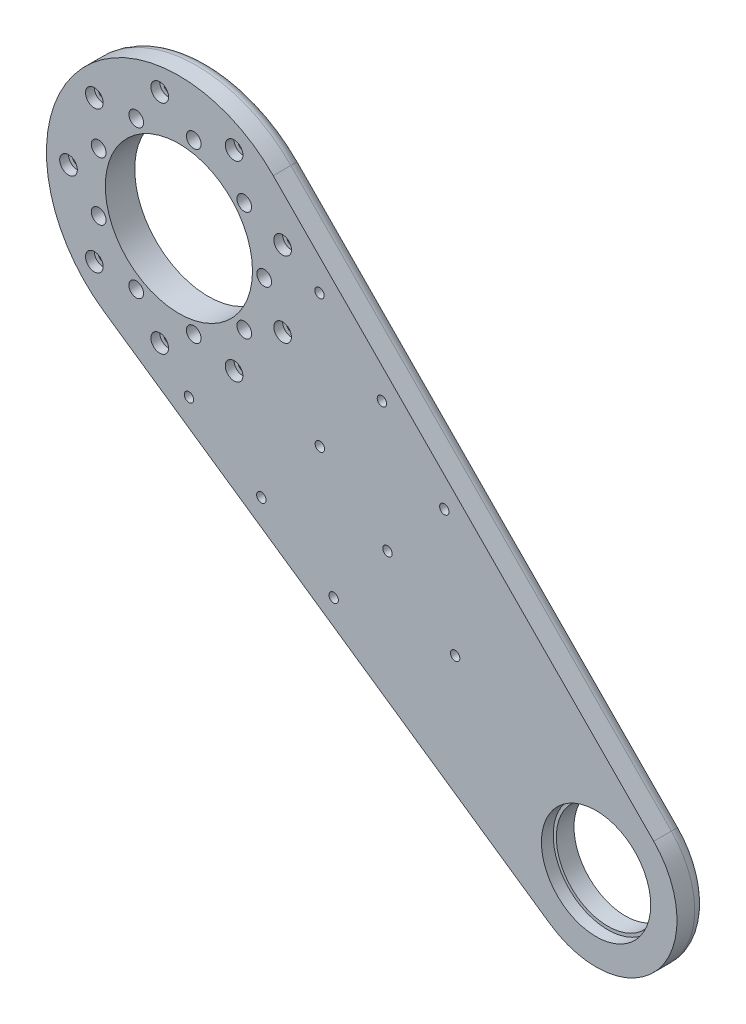
SolidWorks part; units mm, degrees
material "ABS"
ref_plane "Front Plane" through (0, 0, 0) normal (0, 0, 1) x (1, 0, 0)
ref_plane "Top Plane" through (0, 0, 0) normal (0, 1, 0) x (1, 0, 0)
ref_plane "Right Plane" through (0, 0, 0) normal (1, 0, 0) x (0, 0, -1)
sketch "Sketch1" plane through (0, 0, 0) normal (0, 0, 1) x (1, 0, 0)
  line L0 (141.7182, -118.9157) -> (13.1607, -272.1246) construction
  line L1 (26.7138, 26.3177) -> (155.9656, -104.8796) construction
  line L2 (-25.5349, -37.0536) -> (126.1136, -141.5596)
  line L3 (32.0566, 31.5812) -> (161.3084, -99.6161)
  line L4 (-21.2791, -30.878) -> (130.3694, -135.384) construction
  line L5 (0, 0) -> (141.7182, -118.9157) construction
  arc A0 (32.0566, 31.5812) -> (-25.5349, -37.0536) centre (0, 0) ccw
  arc A1 (126.1136, -141.5596) -> (161.3084, -99.6161) centre (141.7182, -118.9157) ccw
  circle A5 centre (0, 0) radius 25 construction
  circle A6 centre (0, 0) radius 37.5 construction
  circle A7 centre (141.7182, -118.9157) radius 17.5
  circle A8 centre (70.8591, -59.4579) radius 1.6
  circle A9 centre (93.8404, -78.7415) radius 1.6
  circle A10 centre (47.8778, -40.1742) radius 1.6
  circle A11 centre (141.7182, -118.9157) radius 20 construction
  circle A12 centre (47.768, 4.9466) radius 1.6
  circle A14 centre (3.4233, -47.9013) radius 1.6
  circle A16 centre (68.9739, -16.2739) radius 1.6
  circle A17 centre (90.1797, -37.4944) radius 1.6
  circle A18 centre (28.0039, -65.1001) radius 1.6
  circle A19 centre (52.5844, -82.2989) radius 1.6
  circle A20 centre (116.8218, -98.0251) radius 1.6 construction
  point P16 (141.7182, -118.9157)
extrude "Boss-Extrude1" add sketch "Sketch1" along normal blind 10
sketch "Sketch2" plane through (0, 0, 10) normal (0, 0, 1) x (1, 0, 0)
  line L0 (0, 0) -> (141.7182, 0) construction
  circle A0 centre (0, 0) radius 25
  circle A2 centre (29, 0) radius 2.5
  circle A3 centre (-37.5, 0) radius 1.6
  circle A4 centre (0, 0) radius 37.5 construction
  circle A5 centre (-28.7267, 24.1045) radius 1.6
  circle A6 centre (-6.5118, 36.9303) radius 1.6
  circle A7 centre (18.75, 32.476) radius 1.6
  circle A8 centre (35.2385, 12.8258) radius 1.6
  circle A9 centre (35.2385, -12.8258) radius 1.6
  circle A10 centre (18.75, -32.476) radius 1.6
  circle A11 centre (-6.5118, -36.9303) radius 1.6
  circle A12 centre (-28.7267, -24.1045) radius 1.6
  circle A13 centre (22.2153, -18.6408) radius 2.5
  circle A14 centre (5.0358, -28.5594) radius 2.5
  circle A15 centre (-14.5, -25.1147) radius 2.5
  circle A16 centre (-27.2511, -9.9186) radius 2.5
  circle A17 centre (-27.2511, 9.9186) radius 2.5
  circle A18 centre (-14.5, 25.1147) radius 2.5
  circle A19 centre (5.0358, 28.5594) radius 2.5
  circle A20 centre (22.2153, 18.6408) radius 2.5
  point P30 (0, 0)
  point P46 (0, 0)
  dimension "D1" = 50
  dimension "D2" = 5
  dimension "D3" = 3.2
  dimension "D4" = 29
  dimension "D5" = 9
  dimension "D6" = 9
extrude "Cut-Extrude1" cut sketch "Sketch2" against normal through all
sketch "Sketch3" plane through (0, 0, 10) normal (0, 0, 1) x (1, 0, 0)
  circle A0 centre (141.7182, -118.9157) radius 18.5625
  dimension "D1" = 37.125
extrude "Cut-Extrude2" cut sketch "Sketch3" against normal blind 4
sketch "Sketch4" plane through (0, 0, 10) normal (0, 0, 1) x (1, 0, 0)
  circle A0 centre (-28.7267, 24.1045) radius 3
  circle A1 centre (-6.5118, 36.9303) radius 3
  circle A2 centre (18.75, 32.476) radius 3
  circle A3 centre (35.2385, 12.8258) radius 3
  circle A4 centre (35.2385, -12.8258) radius 3
  circle A5 centre (18.75, -32.476) radius 3
  circle A6 centre (-6.5118, -36.9303) radius 3
  circle A7 centre (-28.7267, -24.1045) radius 3
  circle A8 centre (-37.5, 0) radius 3
  dimension "D1" = 6
  dimension "D2" = 6
  dimension "D3" = 6
  dimension "D4" = 6
  dimension "D5" = 6
  dimension "D6" = 6
  dimension "D7" = 6
  dimension "D8" = 6
  dimension "D9" = 6
extrude "Cut-Extrude3" cut sketch "Sketch4" against normal blind 3
fillet "Fillet1" radius 4 4 edges at (162.7844, -136.5924, 0) (50.2894, -89.3066, 0) (-34.472, 28.9254, 0) (96.6825, -34.0174, 0)
equation "\"thighLength\"=185"
equation "\"legLength\"=200"
equation "\"m3Thru\"=3.2"
equation "\"m4Thru\"=4.3"
equation "\"D3@Sketch2\"=\"m3Thru\""
equation "\"shoulder5mm\"=5.1"
equation "\"6706out\"=37.125"
equation "\"D1@Sketch3\"=\"6706out\""
equation "\"6706in\"=30"
equation "\"6904out\"=30.125"
equation "\"6904in\"=17"
